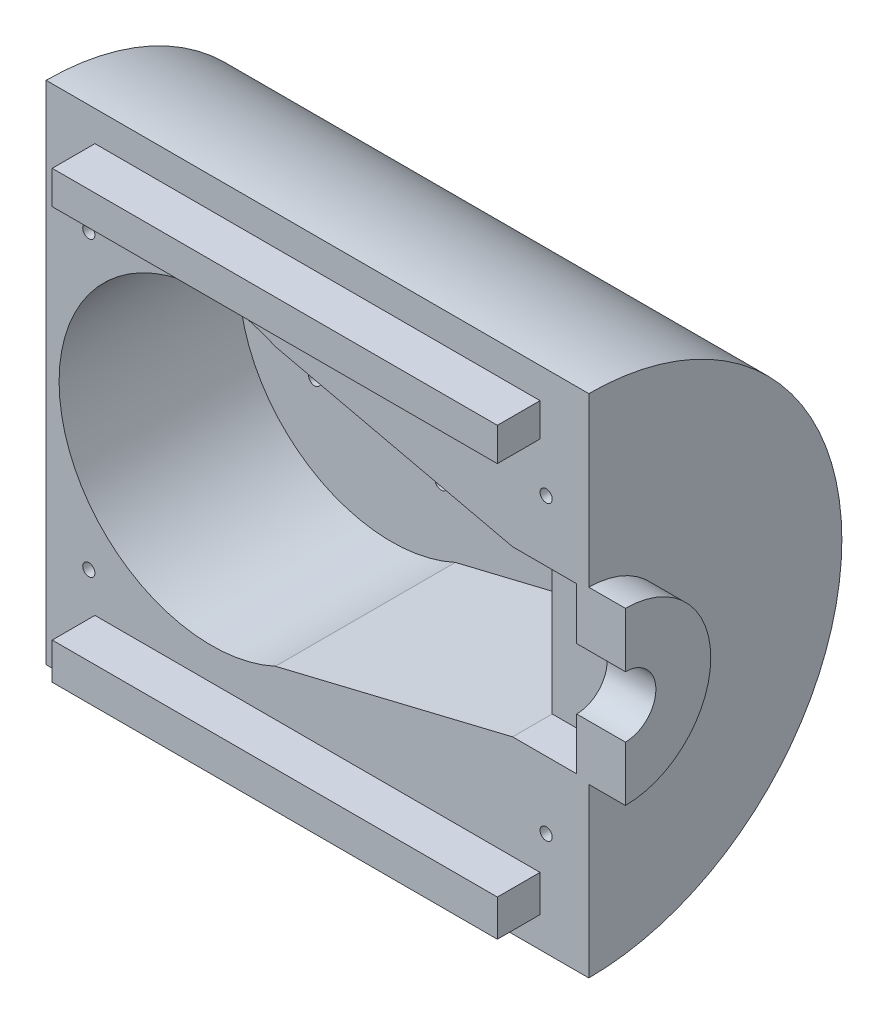
SolidWorks part; units mm, degrees
ref_plane "Front Plane" through (0, 0, 0) normal (0, 0, 1) x (1, 0, 0)
ref_plane "Top Plane" through (0, 0, 0) normal (0, 1, 0) x (1, 0, 0)
ref_plane "Right Plane" through (0, 0, 0) normal (1, 0, 0) x (0, 0, -1)
sketch "Sketch1" plane through (89.9437, 0, 0) normal (1, 0, 0) x (0, 0, -1)
  line L0 (-104.0163, 83.836) -> (-104.0163, 0.836)
  arc A0 (-104.0163, 0.836) -> (-104.0163, 83.836) centre (-104.0163, 42.336) ccw
  dimension "D1" = 83
extrude "Boss-Extrude2" add sketch "Sketch1" against normal blind 87
sketch "Sketch2" plane through (0, 0, 104.0163) normal (0, 0, 1) x (1, 0, 0)
  line L0 (89.9437, 55.836) -> (79.4451, 55.836)
  line L1 (89.9437, 83.836) -> (89.9437, 0.836) construction
  line L2 (79.4451, 55.836) -> (40.5513, 64.8055)
  line L3 (89.9437, 55.836) -> (89.9437, 28.836)
  line L4 (79.4451, 28.836) -> (40.5513, 19.4144)
  line L7 (89.9437, 28.836) -> (79.4451, 28.836)
  arc A0 (40.5513, 64.8055) -> (40.5513, 19.4144) centre (30.0675, 42.1099) ccw construction
  arc A1 (40.5513, 64.8055) -> (40.5513, 19.4144) centre (30.0675, 42.1099) ccw
extrude "Cut-Extrude1" cut sketch "Sketch2" against normal up to vertex (29.5 mm away)
ref_plane "Plane1" through (0, 0, 62.5163) normal (0, 0, -1) x (-1, 0, 0)
sketch "Sketch3" plane through (0, 0, 62.5163) normal (0, 0, -1) x (-1, 0, 0)
  circle A1 centre (-42.6574, 50.2643) radius 1 construction
  circle A2 centre (-42.6574, 50.2643) radius 1
  circle A3 centre (-21.9131, 54.6999) radius 1 construction
  circle A4 centre (-21.9131, 54.6999) radius 1
  circle A5 centre (-38.2218, 29.52) radius 1 construction
  circle A6 centre (-38.2218, 29.52) radius 1
  circle A7 centre (-17.4775, 33.9556) radius 1 construction
  circle A8 centre (-17.4775, 33.9556) radius 1
extrude "Cut-Extrude2" cut sketch "Sketch3" against normal through all
sketch "Sketch4" plane through (0, 0, 62.5163) normal (0, 0, -1) x (-1, 0, 0)
  circle A1 centre (-42.6574, 50.2643) radius 1.7 construction
  circle A2 centre (-42.6574, 50.2643) radius 1.7
  circle A3 centre (-21.9131, 54.6999) radius 1.7 construction
  circle A4 centre (-21.9131, 54.6999) radius 1.7
  circle A5 centre (-38.2218, 29.52) radius 1.7 construction
  circle A6 centre (-38.2218, 29.52) radius 1.7
  circle A7 centre (-17.4775, 33.9556) radius 1.7 construction
  circle A8 centre (-17.4775, 33.9556) radius 1.7
extrude "Cut-Extrude3" cut sketch "Sketch4" against normal blind 10
sketch "Sketch5" plane through (89.9437, 0, 0) normal (1, 0, 0) x (0, 0, -1)
  line L0 (-104.0163, 55.836) -> (-104.0163, 47.336)
  line L1 (-104.0163, 28.836) -> (-104.0163, 37.336)
  line L5 (-104.0163, 55.836) -> (-74.5163, 55.836)
  line L6 (-74.5163, 55.836) -> (-74.5163, 28.836)
  line L7 (-74.5163, 28.836) -> (-104.0163, 28.836)
  line L8 (-104.0163, 28.836) -> (-104.0163, 0.836)
  line L9 (-104.0163, 83.836) -> (-104.0163, 55.836)
  line L13 (-104.0163, 28.836) -> (-104.0163, 0.836)
  line L14 (-104.0163, 83.836) -> (-104.0163, 55.836)
  arc A0 (-104.0163, 37.336) -> (-104.0163, 47.336) centre (-104.0163, 42.336) ccw
  arc A1 (-104.0163, 0.836) -> (-104.0163, 83.836) centre (-104.0163, 42.336) ccw
  arc A2 (-104.0163, 0.836) -> (-104.0163, 83.836) centre (-104.0163, 42.336) ccw
  dimension "D1" = 0
extrude "Boss-Extrude3" add sketch "Sketch5" along normal blind 2
sketch "Sketch6" plane through (91.9437, 0, 0) normal (1, 0, 0) x (0, 0, -1)
  line L0 (-104.0163, 56.336) -> (-104.0163, 47.336)
  line L1 (-104.0163, 28.336) -> (-104.0163, 37.336)
  arc A0 (-104.0163, 28.336) -> (-104.0163, 56.336) centre (-104.0163, 42.336) ccw
  arc A1 (-104.0163, 37.336) -> (-104.0163, 47.336) centre (-104.0163, 42.336) ccw
  dimension "D1" = 14
extrude "Boss-Extrude4" add sketch "Sketch6" along normal blind 6
sketch "Sketch7" plane through (0, 0, 104.0163) normal (0, 0, 1) x (1, 0, 0)
  line L0 (2.9437, 0.836) -> (91.9437, 0.836) construction
  line L1 (10.9437, 78.836) -> (83.9437, 78.836)
  line L2 (10.9437, 78.836) -> (10.9437, 73.3892)
  line L3 (10.9437, 73.3892) -> (83.9437, 73.3892)
  line L4 (83.9437, 78.836) -> (83.9437, 73.3892)
  line L5 (10.9437, 11.836) -> (83.9437, 11.836)
  line L6 (10.9437, 11.836) -> (10.9437, 5.836)
  line L7 (10.9437, 5.836) -> (83.9437, 5.836)
  line L8 (83.9437, 11.836) -> (83.9437, 5.836)
  line L9 (2.9437, 83.836) -> (91.9437, 83.836) construction
  line L10 (10.9437, 73.3892) -> (2.9437, 73.3892) construction
  line L11 (2.9437, 83.836) -> (2.9437, 0.836) construction
  line L12 (83.9437, 73.3892) -> (91.9437, 73.3892) construction
  line L13 (91.9437, 83.836) -> (91.9437, 56.336) construction
  line L15 (10.9437, 11.836) -> (83.9437, 11.836) construction
  line L16 (83.9437, 73.3892) -> (10.9437, 73.3892) construction
  dimension "D1" = 5
  dimension "D2" = 5
  dimension "D4" = 8
extrude "Cut-Extrude4" cut sketch "Sketch7" against normal blind 7
sketch "Sketch8" plane through (0, 0, 62.5163) normal (0, 0, -1) x (-1, 0, 0)
  circle A0 centre (-84.9437, 65.836) radius 1
  circle A1 centre (-84.9437, 17.836) radius 1
  circle A2 centre (-9.9437, 65.836) radius 1
  circle A3 centre (-9.9437, 17.836) radius 1
  circle A4 centre (-84.9437, 65.836) radius 1 construction
  circle A5 centre (-9.9437, 17.836) radius 1 construction
extrude "Cut-Extrude5" cut sketch "Sketch8" against normal through all
sketch "Sketch9" plane through (0, 0, 62.5163) normal (0, 0, -1) x (-1, 0, 0)
  circle A0 centre (-84.9437, 65.836) radius 2.5
  circle A1 centre (-84.9437, 17.836) radius 2.5
  circle A2 centre (-9.9437, 65.836) radius 2.5
  circle A3 centre (-9.9437, 17.836) radius 2.5
  dimension "D1" = 5
extrude "Cut-Extrude6" cut sketch "Sketch9" against normal blind 32
sketch "Sketch11" plane through (0, 0, 74.5163) normal (0, 0, 1) x (1, 0, 0)
  line L0 (79.4451, 28.836) -> (89.9437, 28.836) construction
  line L1 (89.9437, 55.836) -> (79.4451, 55.836)
  line L2 (89.9437, 55.836) -> (89.9437, 28.836)
  line L3 (89.9437, 28.836) -> (79.4451, 28.836)
  line L4 (79.4451, 55.836) -> (79.4451, 28.836)
  line L5 (79.4451, 28.836) -> (89.9437, 28.836) construction
extrude "Boss-Extrude6" add sketch "Sketch11" along normal blind 23
sketch "Sketch12" plane through (0, 0, 97.0163) normal (0, 0, -1) x (-1, 0, 0)
  line L1 (-10.9437, 5.836) -> (-83.9437, 5.836)
  line L2 (-10.9437, 5.836) -> (-10.9437, 11.836)
  line L3 (-10.9437, 11.836) -> (-83.9437, 11.836)
  line L4 (-83.9437, 5.836) -> (-83.9437, 11.836)
  line L5 (-10.9437, 73.3892) -> (-83.9437, 73.3892)
  line L6 (-10.9437, 73.3892) -> (-10.9437, 78.836)
  line L7 (-10.9437, 78.836) -> (-83.9437, 78.836)
  line L8 (-83.9437, 73.3892) -> (-83.9437, 78.836)
extrude "Boss-Extrude7" add sketch "Sketch12" against normal blind 14
